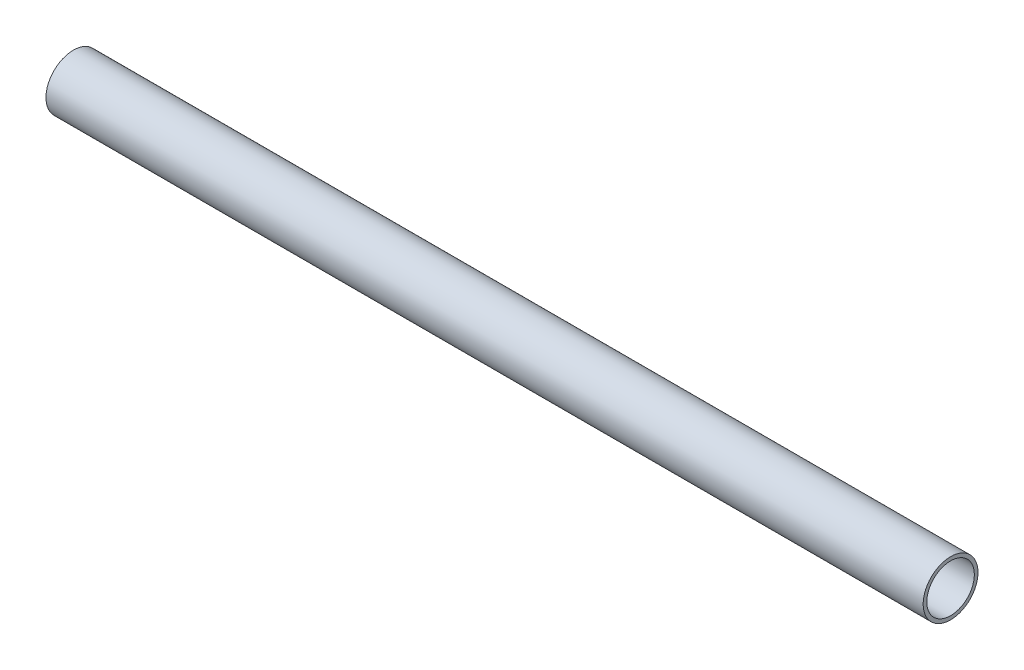
SolidWorks part; units mm, degrees
ref_plane "Front Plane" through (0, 0, 0) normal (0, 0, 1) x (1, 0, 0)
ref_plane "Top Plane" through (0, 0, 0) normal (0, 1, 0) x (1, 0, 0)
ref_plane "Right Plane" through (0, 0, 0) normal (1, 0, 0) x (0, 0, -1)
sketch "草图1" plane through (0, 0, 0) normal (1, 0, 0) x (0, 0, -1)
  circle A0 centre (0, 0) radius 6.5
  circle A1 centre (0, 0) radius 7.5
extrude "凸台-拉伸1" add sketch "草图1" along normal blind 240
